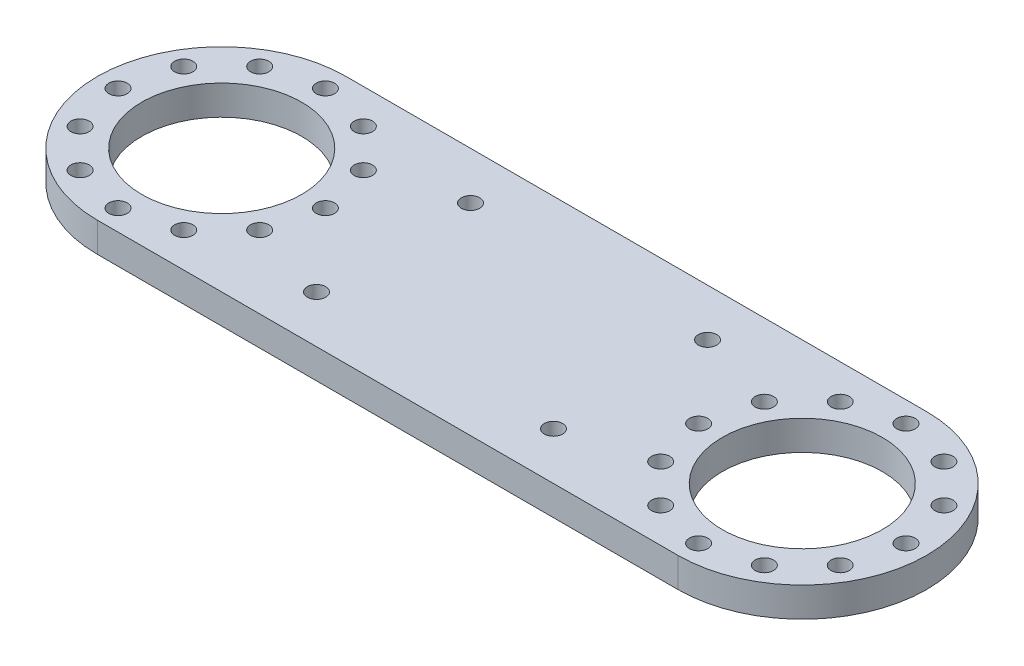
SolidWorks part; units mm, degrees
material "Thornel Mat VMA"
ref_plane "前视基准面" through (0, 0, 0) normal (0, 0, 1) x (1, 0, 0)
ref_plane "上视基准面" through (0, 0, 0) normal (0, 1, 0) x (1, 0, 0)
ref_plane "右视基准面" through (0, 0, 0) normal (1, 0, 0) x (0, 0, -1)
other "Configuration Table"
sketch "草图1" plane through (0, 0, 0) normal (0, 1, 0) x (1, 0, 0)
  line L0 (-49, 0) -> (49, 0) construction
  line L1 (-49, 21) -> (49, 21)
  line L2 (-49, -21) -> (49, -21)
  line L3 (0, -26.8061) -> (0, 32.763) construction
  arc A0 (-49, 21) -> (-49, -21) centre (-49, 0) ccw
  arc A1 (49, -21) -> (49, 21) centre (49, 0) ccw
  circle A2 centre (-49, 0) radius 13.5
  circle A3 centre (-49, 17.5) radius 1.55
  circle A4 centre (-20, 13) radius 1.55
  circle A5 centre (-20, -13) radius 1.55
  circle A6 centre (-40.25, 15.1554) radius 1.55
  circle A7 centre (-33.8446, 8.75) radius 1.55
  circle A8 centre (-31.5, 0) radius 1.55
  circle A9 centre (-33.8446, -8.75) radius 1.55
  circle A10 centre (-40.25, -15.1554) radius 1.55
  circle A11 centre (-49, -17.5) radius 1.55
  circle A12 centre (-57.75, -15.1554) radius 1.55
  circle A13 centre (-64.1554, -8.75) radius 1.55
  circle A14 centre (-66.5, 0) radius 1.55
  circle A15 centre (-64.1554, 8.75) radius 1.55
  circle A16 centre (-57.75, 15.1554) radius 1.55
  circle A17 centre (57.75, 15.1554) radius 1.55
  circle A18 centre (64.1554, 8.75) radius 1.55
  circle A19 centre (66.5, 0) radius 1.55
  circle A20 centre (64.1554, -8.75) radius 1.55
  circle A21 centre (57.75, -15.1554) radius 1.55
  circle A22 centre (49, -17.5) radius 1.55
  circle A23 centre (40.25, -15.1554) radius 1.55
  circle A24 centre (33.8446, -8.75) radius 1.55
  circle A25 centre (31.5, 0) radius 1.55
  circle A26 centre (40.25, 15.1554) radius 1.55
  circle A27 centre (20, -13) radius 1.55
  circle A28 centre (20, 13) radius 1.55
  circle A29 centre (49, 17.5) radius 1.55
  circle A30 centre (49, 0) radius 13.5
  circle A31 centre (33.8446, 8.75) radius 1.55
  point P2 (0, 0)
  point P40 (-49, 0)
  point P67 (49, 0)
  dimension "D2" = 21
  dimension "D3" = 27
  dimension "D5" = 3.1
  dimension "D9" = 3.1
  dimension "D1" = 98
  dimension "D4" = 17.5
  dimension "D6" = 26
  dimension "D7" = 20
  dimension "D8" = 13
  dimension "D10" = 12
extrude "凸台-拉伸1" add sketch "草图1" along normal blind 5
